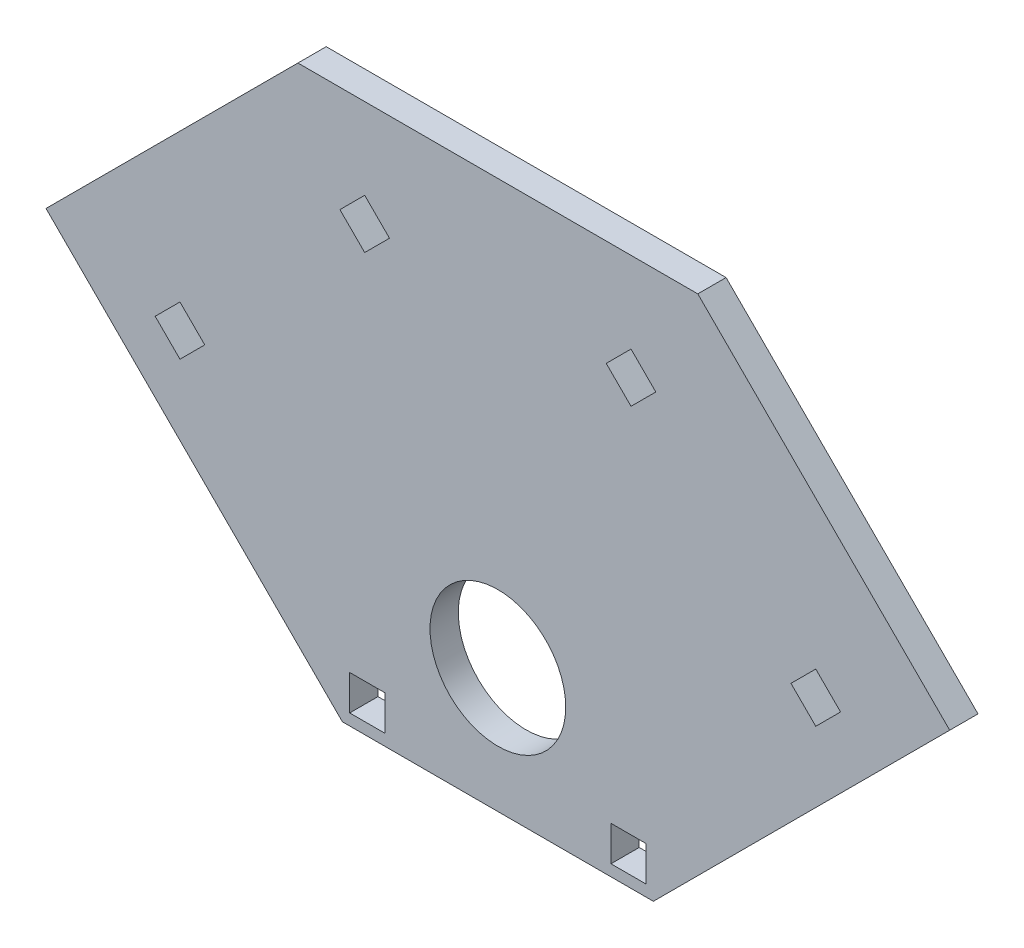
SolidWorks part; units mm, degrees
material "ABS"
ref_plane "Front Plane" through (0, 0, 0) normal (0, 0, 1) x (1, 0, 0)
ref_plane "Top Plane" through (0, 0, 0) normal (0, 1, 0) x (1, 0, 0)
ref_plane "Right Plane" through (0, 0, 0) normal (1, 0, 0) x (0, 0, -1)
sketch "Sketch3" plane through (0, 0, 0) normal (0, 0, 1) x (1, 0, 0)
  line L8 (0, 0) -> (136.4293, 136.4293) construction
  line L9 (0, 0) -> (0, 136.4293) construction
  line L10 (0, 0) -> (-136.4293, 136.4293) construction
  line L20 (-15.2843, -13) -> (15.2843, -13) construction
  line L23 (-15.2843, -13) -> (-69.2965, 41.0122) construction
  line L25 (15.2843, -13) -> (69.2965, 41.0122) construction
  line L27 (-69.2965, 41.0122) -> (-41.0122, 69.2965)
  line L29 (41.0122, 69.2965) -> (69.2965, 41.0122)
  line L32 (-15.2843, -13) -> (15.2843, -13) construction
  line L34 (-27.4975, -22) -> (27.4975, -22)
  line L36 (-27.4975, -22) -> (-79.9031, 30.4056)
  line L37 (-79.9031, 30.4056) -> (-69.2965, 41.0122)
  line L42 (-41.0122, 69.2965) -> (-31.5262, 59.8104) construction
  line L47 (27.4975, -22) -> (79.9031, 30.4056)
  line L48 (79.9031, 30.4056) -> (69.2965, 41.0122)
  line L49 (0, 0) -> (0, -22) construction
  line L50 (-41.0122, 69.2965) -> (-35.3553, 74.9533)
  line L51 (-35.3553, 74.9533) -> (35.3553, 74.9533)
  line L52 (35.3553, 74.9533) -> (41.0122, 69.2965)
  line L53 (41.0122, 69.2965) -> (23.1501, 51.4344) construction
  line L54 (-35.3553, 74.9533) -> (-11.8413, 51.4393) construction
  line L55 (35.3553, 74.9533) -> (27.1196, 66.7176) construction
  line L56 (-60.5991, 23.5467) -> (-56.215, 27.9307)
  line L57 (-56.215, 27.9307) -> (-51.8309, 23.5467)
  line L58 (-51.8309, 23.5467) -> (-56.215, 19.1626)
  line L59 (-56.215, 19.1626) -> (-60.5991, 23.5467)
  line L60 (-27.9307, 56.215) -> (-23.5467, 60.5991)
  line L61 (-23.5467, 60.5991) -> (-19.1626, 56.215)
  line L62 (-19.1626, 56.215) -> (-23.5467, 51.8309)
  line L63 (-23.5467, 51.8309) -> (-27.9307, 56.215)
  line L64 (19.1626, 56.215) -> (23.5467, 51.8309)
  line L65 (-26.2, -20) -> (-20, -20)
  line L66 (-26.2, -20) -> (-26.2, -13.8)
  line L67 (-26.2, -13.8) -> (-20, -13.8)
  line L68 (-20, -20) -> (-20, -13.8)
  line L69 (-26.2, -20) -> (-20, -13.8) construction
  line L70 (-26.2, -13.8) -> (-20, -20) construction
  line L71 (23.5467, 51.8309) -> (27.9307, 56.215)
  line L72 (27.9307, 56.215) -> (23.5467, 60.5991)
  line L73 (23.5467, 60.5991) -> (19.1626, 56.215)
  line L74 (51.8309, 23.5467) -> (56.215, 19.1626)
  line L75 (56.215, 19.1626) -> (60.5991, 23.5467)
  line L76 (60.5991, 23.5467) -> (56.215, 27.9307)
  line L77 (56.215, 27.9307) -> (51.8309, 23.5467)
  line L78 (26.2, -20) -> (20, -20)
  line L79 (26.2, -20) -> (26.2, -13.8)
  line L80 (26.2, -13.8) -> (20, -13.8)
  line L81 (20, -20) -> (20, -13.8)
  circle A0 centre (0, 0) radius 12
  point P7 (55.1543, 55.1543)
  point P15 (-55.1543, 55.1543)
  point P32 (-23.1, -16.9)
  dimension "crankshaftBearingOD" = 24
  dimension "D8" = 45
  dimension "D10" = 45
  dimension "D2" = 78
  dimension "D3" = 78
  dimension "D4" = 40
  dimension "D5" = 40
  dimension "D6" = 13
  dimension "D7" = 22
  dimension "D9" = 8
  dimension "D11" = 15
  dimension "D12" = 159.8061
  dimension "D13" = 96.9533
  dimension "D15" = 18.5
  dimension "D16" = 6.2
  dimension "D18" = 18.5
  dimension "D19" = 6.2
  dimension "D20" = 6.2
  dimension "D21" = 2
  dimension "D14" = 20
extrude "Boss-Extrude1" add sketch "Sketch3" along normal blind 5
equation "\"crankshaftBearingOD@Sketch3\"=24.00mm"
